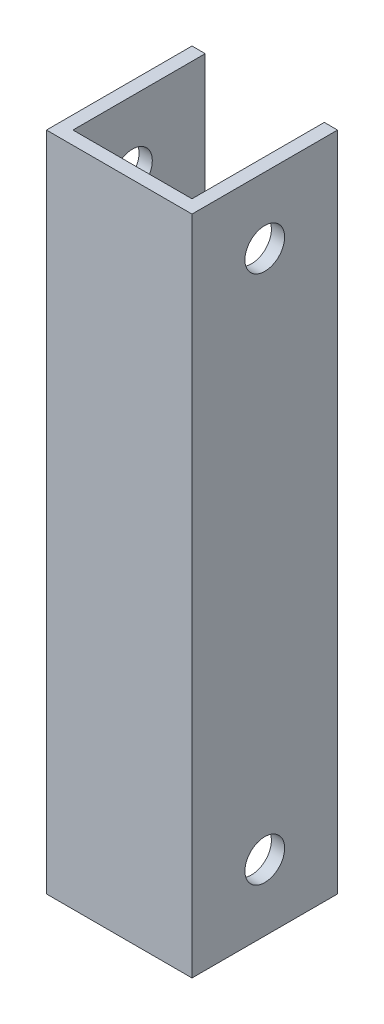
SolidWorks part; units mm, degrees
ref_plane "Alzado" through (0, 0, 0) normal (0, 0, 1) x (1, 0, 0)
ref_plane "Planta" through (0, 0, 0) normal (0, 1, 0) x (1, 0, 0)
ref_plane "Vista lateral" through (0, 0, 0) normal (1, 0, 0) x (0, 0, -1)
sketch "Croquis1" plane through (0, 0, 0) normal (0, 1, 0) x (1, 0, 0)
  line L0 (-9, 11) -> (-9, -9)
  line L1 (-11, 11) -> (-9, 11)
  line L2 (-11, 11) -> (-11, -11)
  line L3 (-11, -11) -> (11, -11)
  line L4 (11, 11) -> (11, -11)
  line L5 (-11, 11) -> (11, -11) construction
  line L6 (-11, -11) -> (11, 11) construction
  line L7 (-9, -9) -> (9, -9)
  line L8 (9, -9) -> (9, 11)
  line L9 (9, 11) -> (11, 11)
  point P0 (0, 0)
  dimension "D1" = 22
  dimension "D2" = 22
  dimension "D3" = 2
  dimension "D4" = 2
  dimension "D5" = 2
extrude "Saliente-Extruir1" add sketch "Croquis1" along normal blind 100
sketch "Croquis2" plane through (11, 0, 0) normal (1, 0, 0) x (0, 0, -1)
  line L0 (-11, 20) -> (11, 20) construction
  line L1 (-11, 100) -> (-11, 0) construction
  line L2 (11, 100) -> (11, 0) construction
  line L3 (-11, 0) -> (11, 0) construction
  line L4 (0, 20) -> (0, 0) construction
  line L5 (-11, 10) -> (11, 10) construction
  circle A0 centre (0, 10) radius 3
  dimension "D3" = 6
  dimension "D1" = 20
  dimension "D2" = 10
extrude "Cortar-Extruir1" cut sketch "Croquis2" against normal blind 100
sketch "Croquis3" plane through (11, 0, 0) normal (1, 0, 0) x (0, 0, -1)
  line L0 (-11, 80) -> (11, 80) construction
  line L1 (-11, 100) -> (-11, 0) construction
  line L2 (11, 100) -> (11, 0) construction
  line L3 (-11, 100) -> (11, 100) construction
  line L4 (0, 100) -> (0, 80) construction
  line L5 (-11, 90) -> (11, 90) construction
  circle A0 centre (0, 90) radius 3
  dimension "D3" = 6
  dimension "D1" = 20
  dimension "D2" = 10
extrude "Cortar-Extruir2" cut sketch "Croquis3" against normal through all
